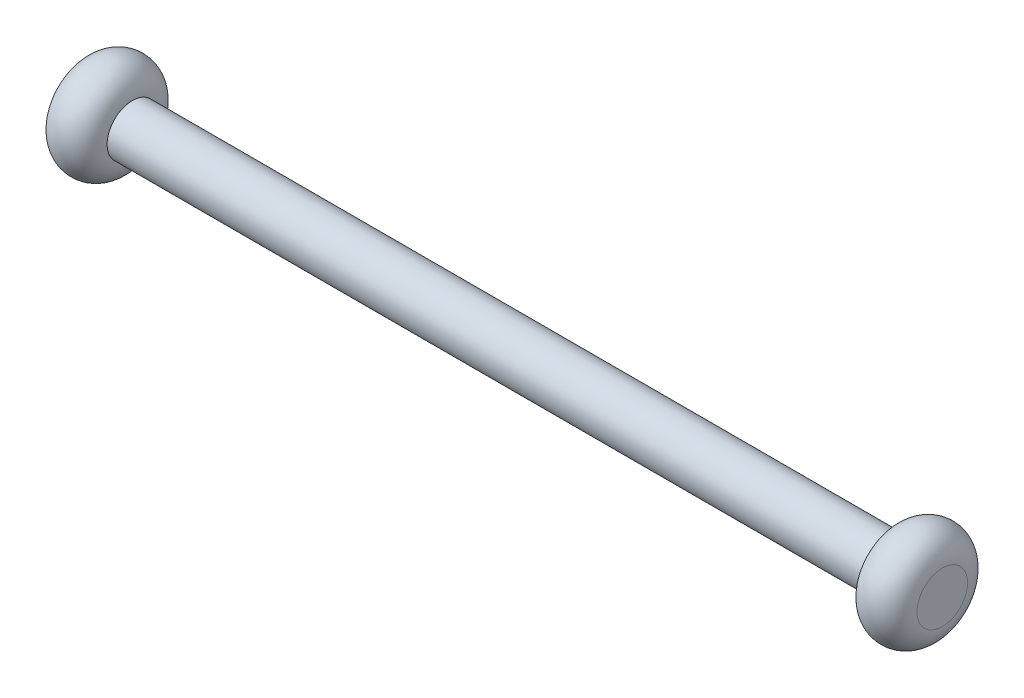
SolidWorks part; units mm, degrees
ref_plane "Front Plane" through (0, 0, 0) normal (0, 0, 1) x (1, 0, 0)
ref_plane "Top Plane" through (0, 0, 0) normal (0, 1, 0) x (1, 0, 0)
ref_plane "Right Plane" through (0, 0, 0) normal (1, 0, 0) x (0, 0, -1)
sketch "Sketch2" plane through (0, 0, 0) normal (0, 0, 1) x (1, 0, 0)
  line L0 (-85, 0) -> (85, 0)
  line L1 (0, 0) -> (0, 36.621) construction
  line L2 (-85, 0) -> (-85, 5)
  line L3 (75, 5) -> (-75, 5)
  line L4 (85, 0) -> (85, 5)
  arc A0 (-75, 5) -> (-85, 5) centre (-80, 5) ccw
  arc A1 (75, 5) -> (85, 5) centre (80, 5) cw
  point P4 (0, 0)
  point P12 (0, 5)
  dimension "D2" = 5
  dimension "D3" = 5
  dimension "D1" = 170
revolve "Revolve1" add sketch "Sketch2" angle 360 about L0
